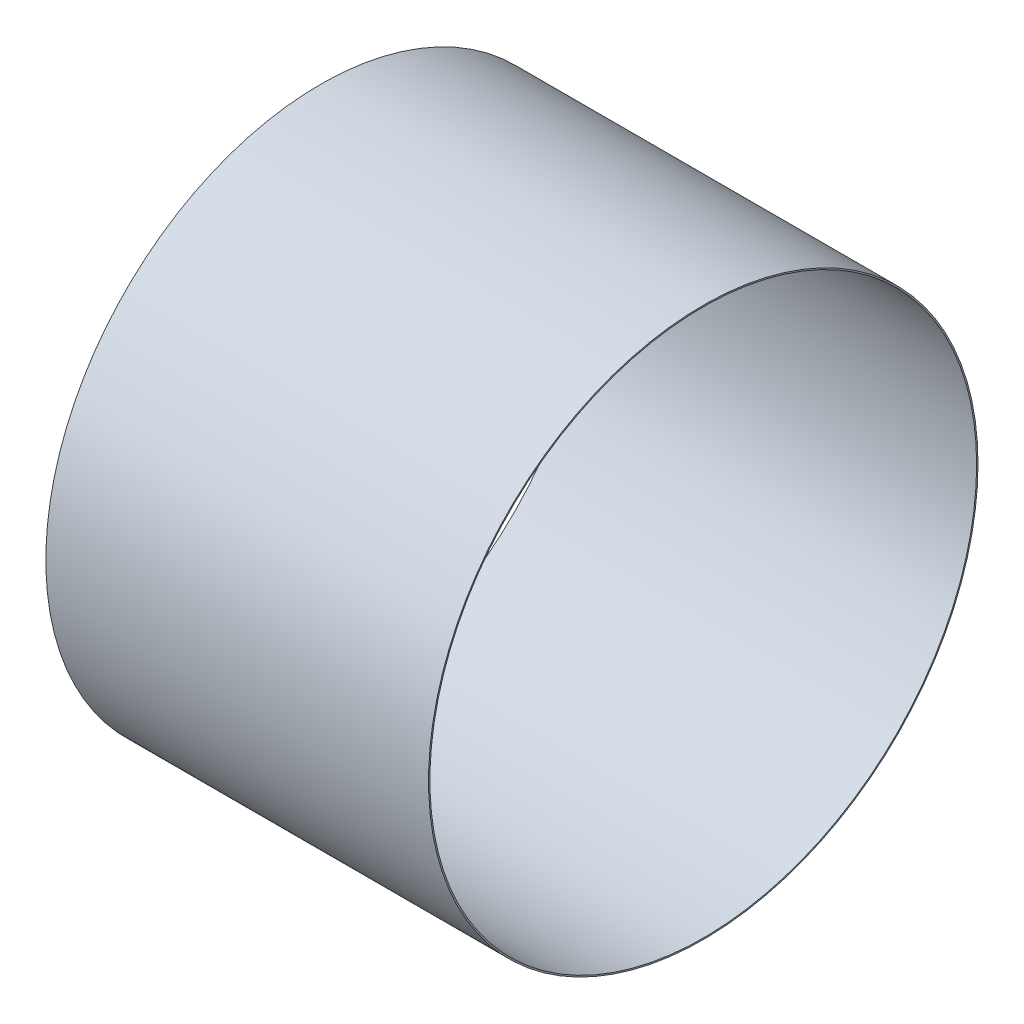
SolidWorks part; units mm, degrees
ref_plane "Front Plane" through (0, 0, 0) normal (0, 0, 1) x (1, 0, 0)
ref_plane "Top Plane" through (0, 0, 0) normal (0, 1, 0) x (1, 0, 0)
ref_plane "Right Plane" through (0, 0, 0) normal (1, 0, 0) x (0, 0, -1)
sketch "Sketch1" plane through (0, 0, 0) normal (1, 0, 0) x (0, 0, -1)
  circle A0 centre (0, 0) radius 635
extrude "Extrude-Thin2" add sketch "Sketch1" along normal blind 889 thin
sketch "Sketch2" plane through (0, 0, 0) normal (1, 0, 0) x (0, 0, -1)
  circle A0 centre (0, 0) radius 635 construction
